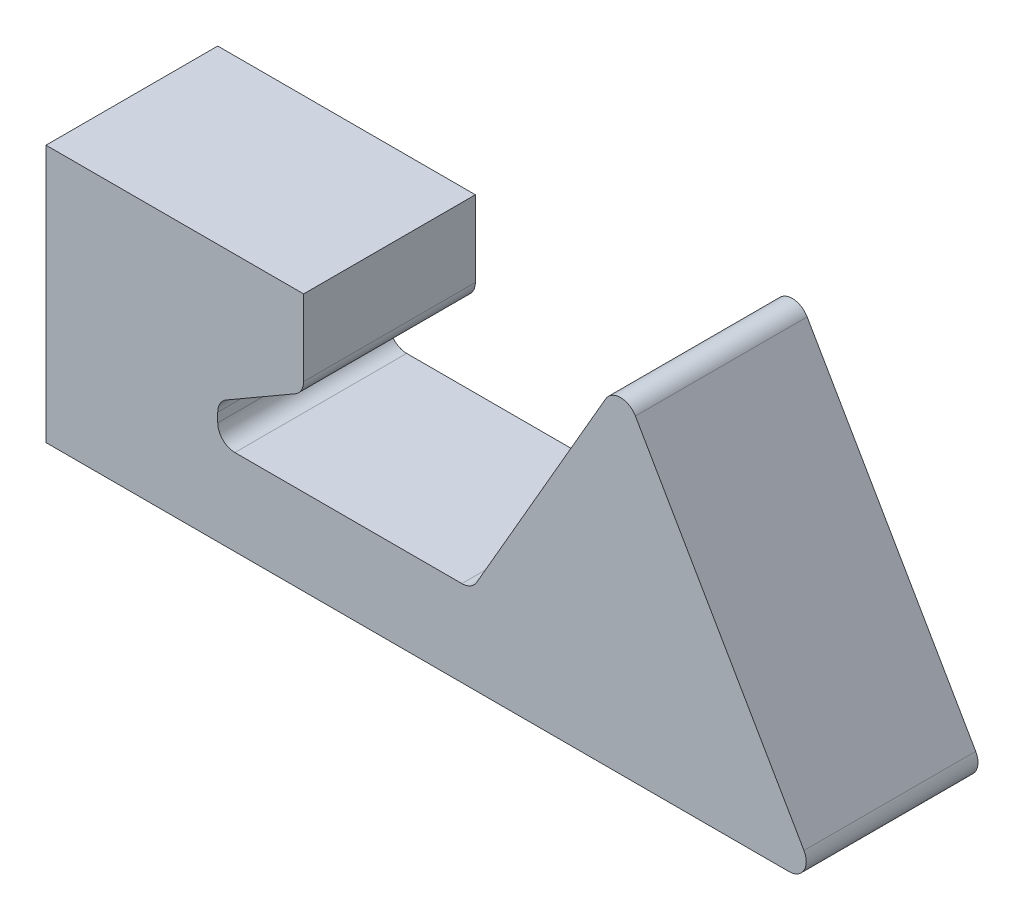
SolidWorks part; units mm, degrees
ref_plane "Front Plane" through (0, 0, 0) normal (0, 0, 1) x (1, 0, 0)
ref_plane "Top Plane" through (0, 0, 0) normal (0, 1, 0) x (1, 0, 0)
ref_plane "Right Plane" through (0, 0, 0) normal (1, 0, 0) x (0, 0, -1)
sketch "Sketch1" plane through (0, 0, 0) normal (0, 0, 1) x (1, 0, 0)
  line L0 (0, 0) -> (90, 0)
  line L1 (90, 0) -> (66.906, 40)
  line L2 (66.906, 40) -> (49.5855, 10)
  line L3 (49.5855, 10) -> (20, 10)
  line L4 (20, 10) -> (20, 14.2265)
  line L5 (20, 14.2265) -> (30, 20)
  line L6 (30, 20) -> (30, 30)
  line L7 (30, 30) -> (0, 30)
  line L8 (0, 30) -> (0, 0)
  dimension "D1" = 60
  dimension "D2" = 60
  dimension "D3" = 30
  dimension "D4" = 30
  dimension "D5" = 40
  dimension "D6" = 10
  dimension "D7" = 10
  dimension "D8" = 10
  dimension "D9" = 90
extrude "Boss-Extrude1" add sketch "Sketch1" along normal blind 20
fillet "Fillet1" radius 2 6 edges at (30, 20, 10) (20, 14.2265, 10) (20, 10, 10) (49.5855, 10, 10) (66.906, 40, 10) (90, 0, 10)
